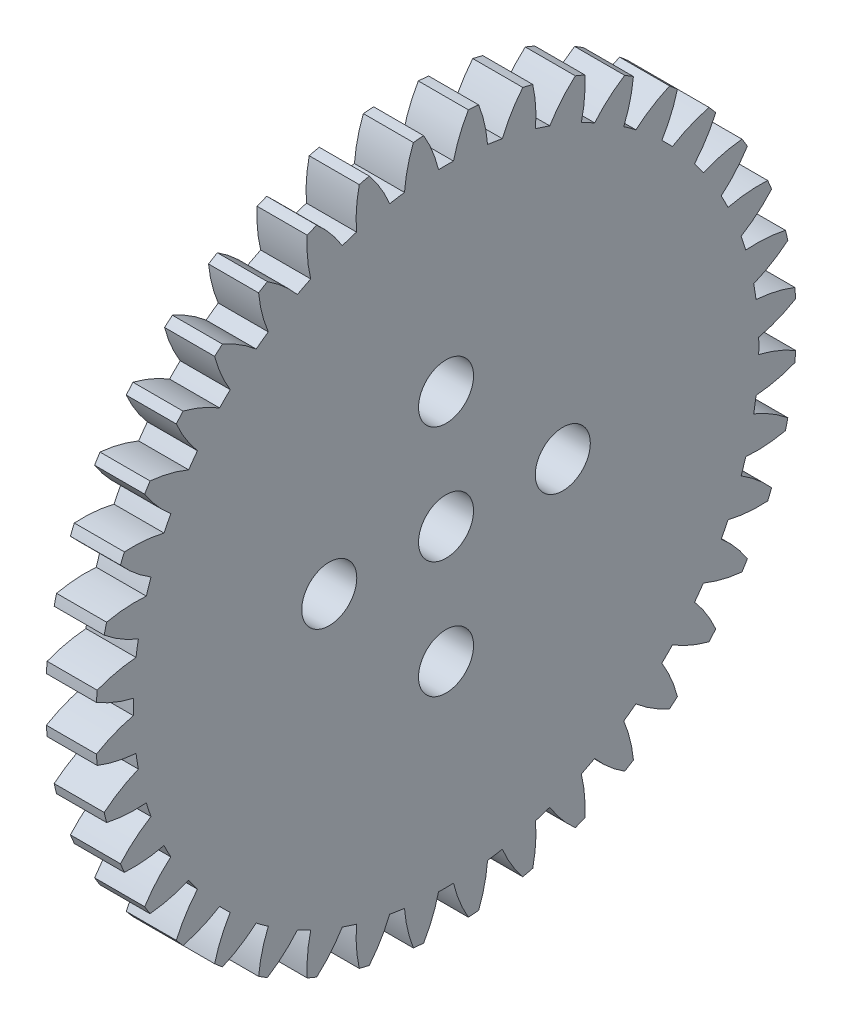
SolidWorks part; units mm, degrees
ref_plane "Plane1" through (0, 0, 0) normal (0, 0, 1) x (1, 0, 0)
ref_plane "Plane2" through (0, 0, 0) normal (0, 1, 0) x (1, 0, 0)
ref_plane "Plane3" through (0, 0, 0) normal (1, 0, 0) x (0, 0, -1)
other "Configuration Table"
sketch "HoldingSke" plane through (0, 0, 0) normal (0, 1, 0) x (1, 0, 0)
  line L0 (0, 0) -> (0.766, -0.6428)
  line L1 (-15, 0) -> (100, 0) construction
  line L2 (0, 0) -> (-2.1039, 2.3779)
  line L3 (0, 0) -> (-11.863, 4.5341)
  line L4 (0, 0) -> (6.6156, 5.5511)
  line L5 (0, 0) -> (-46.8476, -17.4728)
  line L6 (0, 0) -> (-2.4869, -1.6779)
  line L7 (-2.1039, 2.3779) -> (8.6586, 51.2059)
  line L8 (-76.2, 54.61) -> (-76.1, 54.61)
  line L9 (-71.009, 38.7566) -> (-53.1078, 45.2721)
  line L10 (-76.2, 71.12) -> (104.1128, 71.12)
  line L11 (0, 0) -> (-3, 0)
  line L12 (-76.2, 101.6) -> (-76.162, 101.6)
  line L13 (24.9733, 27.94) -> (52.9518, 28.4284)
  line L14 (24.9733, 27.94) -> (24.9743, 27.94)
  line L15 (24.9733, 27.94) -> (100.4006, 29.5858)
  line L16 (-63.627, -1) -> (-12.827, -1)
  circle A0 centre (0, 0) radius 0.5
  circle A1 centre (0, 0) radius 18.749
  circle A2 centre (0, 0) radius 37.5
  circle A3 centre (0, 0) radius 0.5
  dimension "MHD" = 37.498
  dimension "Hub_dia" = 75
  dimension "Bore" = 1
  dimension "MBD" = 1
  dimension "Num_teeth" = 40
  dimension "Pitch" = 1
  dimension "Overall_len" = 50
  dimension "Show_teeth" = 40
  dimension "Thickness" = 3
  dimension "OAL" = 50.0001
  dimension "T_dim" = 0.1
  dimension "Ap" = 20
  dimension "H" = 19.05
  dimension "Pitch_radius" = 180.3128
  dimension "Width" = 3
  dimension "Backlash" = 0.038
  dimension "Addendum_fac" = 1
  dimension "Dedendum_fac" = 1.25
  dimension "Clearance_fac" = 0.25
  dimension "Dedendum_add" = 0.001
  dimension "Module" = 1
sketch "BasProSke" plane through (0, 0, 0) normal (0, 1, 0) x (1, 0, 0)
  line L0 (-10, 0) -> (60, 0) construction
  line L1 (0, 0) -> (0, 21)
  line L2 (0, 0) -> (3, 0)
  line L3 (3, 0) -> (3, 21)
  line L4 (3, 21) -> (0, 21)
  dimension "Thickness" = 3
  dimension "Diameter" = 42
revolve "Base-Revolve" add sketch "BasProSke" angle 360 about L0
sketch "TooCutSke" plane through (0, 0, 0) normal (1, 0, 0) x (0, 0, -1)
  line L1 (0, 0) -> (0, 107) construction
  line L2 (0, 0) -> (-0.8517, 19.9819) construction
  line L3 (0, 0) -> (-3.1363, 39.8509) construction
  line L4 (-0.8517, 19.9819) -> (-1.5682, 19.9255) construction
  arc A0 (0.4487, 18.7436) -> (-0.4487, 18.7436) centre (0, 0) ccw
  arc A1 (1.3547, 20.9817) -> (-1.3547, 20.9817) centre (0, 0) ccw
  circle A2 centre (0, 0) radius 20 construction
  circle A3 centre (0, 0) radius 18.7939 construction
  arc A4 (-0.4487, 18.7436) -> (-1.3547, 20.9817) centre (-8.2322, 16.895) ccw
  arc A5 (1.3547, 20.9817) -> (0.4487, 18.7436) centre (8.2322, 16.895) ccw
  dimension "Root_dia" = 37.498
  dimension "Overcut_dia" = 42.0508
  dimension "Pitch_dia" = 40
  dimension "Base_dia" = 37.5877
  dimension "Flank_rad" = 8
  dimension "Half_ang" = 4.5
  dimension "Half_CT" = 0.7187
extrude "ToothCut" cut sketch "TooCutSke" along normal through all
fillet "Breaks" [suppressed] radius 0.02
fillet "RootFillets" [suppressed] radius 0.251
pattern_circular "TeethCuts" count 40 every 9 about axis through (-10, 0, 0) along (1, 0, 0) of "ToothCut", "RootFillets", "Breaks"
sketch "HubNeaOneSke" plane through (0, 0, 0) normal (-1, 0, 0) x (0, 0, 1)
  circle A0 centre (0, 0) radius 18.749
  dimension "Diameter" = 37.498
extrude "HubNearOne" [suppressed] add sketch "HubNeaOneSke" along normal blind 47.0001
sketch "HubNeaBotSke" plane through (0, 0, 0) normal (-1, 0, 0) x (0, 0, 1)
  circle A0 centre (0, 0) radius 18.749
  dimension "Diameter" = 37.498
extrude "HubNearBoth" [suppressed] add sketch "HubNeaBotSke" along normal blind 23.5
ref_plane "FarPln" through (3, 0, 0) normal (1, 0, 0) x (0, 0, -1)
sketch "HubFarSke" plane through (3, 0, 0) normal (1, 0, 0) x (0, 0, -1)
  circle A0 centre (0, 0) radius 18.749
  dimension "Diameter" = 37.498
extrude "HubFar" [suppressed] add sketch "HubFarSke" along normal blind 23.5
sketch "BorSke" plane through (0, 0, 0) normal (1, 0, 0) x (0, 0, -1)
  circle A0 centre (0, 0) radius 0.5
  dimension "Diameter" = 1
extrude "Bore" cut sketch "BorSke" along normal mid plane 100.0001
sketch "KeySke" plane through (0, 0, 0) normal (1, 0, 0) x (0, 0, -1)
  line L0 (-0.05, 0) -> (-0.05, 0.6)
  line L1 (-0.05, 0.6) -> (0.05, 0.6)
  line L2 (0.05, 0.6) -> (0.05, 0)
  line L3 (0, 0) -> (0, 34) construction
  line L4 (-0.05, 0) -> (0.05, 0)
  dimension "Offset" = 0.6
  dimension "Width" = 0.1
extrude "Keyway" [suppressed] cut sketch "KeySke" along normal mid plane 100.0001
pattern_circular "Keyway2" [suppressed] count 2 every 90 about axis through (-10, 0, 0) along (1, 0, 0)
sketch "草图1" plane through (3, 0, 0) normal (1, 0, 0) x (0, 0, -1)
  circle A0 centre (0, 0) radius 20
  dimension "D1" = 40
sketch "草图2" plane through (3, 0, 0) normal (1, 0, 0) x (0, 0, -1)
  circle A0 centre (0, 0) radius 1.65
  circle A1 centre (0, 0) radius 7 construction
  circle A2 centre (7, 0) radius 1.65
  circle A3 centre (-7, 0) radius 1.65
  circle A4 centre (0, 7) radius 1.65
  circle A5 centre (0, -7) radius 1.65
  dimension "D1" = 3.3
  dimension "D2" = 14
  dimension "D3" = 3.3
  dimension "D4" = 3.3
  dimension "D5" = 3.3
  dimension "D6" = 3.3
extrude "切除-拉伸1" cut sketch "草图2" against normal up to next
equation "' \"Module@HoldingSke\" = 6.35"
equation "' \"Num_teeth@HoldingSke\" = 12"
equation "' \"Ap@HoldingSke\" =  20"
equation "' \"Ap@HoldingSke\" = 20"
equation "' \"Width@HoldingSke\" = 0.5 * 25.4"
equation "' \"Hub_dia@HoldingSke\"= 1 * 25.4"
equation "' \"Hub_dia@HoldingSke\" = 1 * 25.4"
equation "' \"Overall_len@HoldingSke\" = 1.0 * 25.4"
equation "' \"Bore@HoldingSke\" = 0.75 * 25.4"
equation "' \"T_dim@HoldingSke\" = 0.1 * 25.4"
equation "' \"Width@KeySke\" = 0.25 * 25.4"
equation "' \"Show_teeth@HoldingSke\" = 13"
equation "' \"Backlash@HoldingSke\" = 0.009 * 25.4"
equation "' \"Addendum_fac@HoldingSke\" = 1.0"
equation "' \"Dedendum_fac@HoldingSke\" = 1.25"
equation "' \"Dedendum_add@HoldingSke\" = 0.00005 * 25.4"
equation "' \"Clearance_fac@HoldingSke\" = 0.25"
equation "\"Pitch@HoldingSke\" = 1 / \"Module@HoldingSke\""
equation "\"Overcut_dia@TooCutSke\" = (\"Num_teeth@HoldingSke\" + 2 * \"Addendum_fac@HoldingSke\") / \"Pitch@HoldingSke\" + 0.002 * 25.4"
equation "\"Pitch_dia@TooCutSke\" = \"Num_teeth@HoldingSke\" / \"Pitch@HoldingSke\""
equation "\"Base_dia@TooCutSke\" = \"Num_teeth@HoldingSke\" / \"Pitch@HoldingSke\" * cos((\"Ap@HoldingSke\"  * 3.14159265 / 180))"
equation "\"Root_dia@TooCutSke\" = (\"Num_teeth@HoldingSke\" + 2) / \"Pitch@HoldingSke\" - 2 * (\"Addendum_fac@HoldingSke\" + \"Dedendum_fac@HoldingSke\") / \"Pitch@HoldingSke\" - \"Dedendum_add@HoldingSke\" * 2"
equation "\"Half_ang@TooCutSke\" = 180 / \"Num_teeth@HoldingSke\""
equation "\"Half_CT@TooCutSke\" = \"Num_teeth@HoldingSke\" / \"Pitch@HoldingSke\" * sin((3.14159265 / 2 / \"Num_teeth@HoldingSke\")) / 2 - 7 * \"Backlash@HoldingSke\" / 4"
equation "\"Flank_rad@TooCutSke\" = \"Num_teeth@HoldingSke\" / \"Pitch@HoldingSke\" / 5"
equation "\"Radius@RootFillets\" = \"Clearance_fac@HoldingSke\" / \"Pitch@HoldingSke\" + \"Dedendum_add@HoldingSke\""
equation "\"Break_rad@Breaks\" = 0.02 / \"Pitch@HoldingSke\""
equation "\"Thickness@HoldingSke\" = \"Width@HoldingSke\""
equation "\"OAL@HoldingSke\" = \"Thickness@HoldingSke\""
equation "\"MHD@HoldingSke\" = (\"Num_teeth@HoldingSke\" + 2) / \"Pitch@HoldingSke\" - 2 * (\"Addendum_fac@HoldingSke\" + \"Dedendum_fac@HoldingSke\")  / \"Pitch@HoldingSke\" - \"Dedendum_add@HoldingSke\" * 2"
equation "\"MBD@HoldingSke\" = (\"Num_teeth@HoldingSke\" + 2) / \"Pitch@HoldingSke\" - 2 * (\"Addendum_fac@HoldingSke\" + \"Dedendum_fac@HoldingSke\")  / \"Pitch@HoldingSke\" - \"Dedendum_add@HoldingSke\" * 2 - 0.002 * 25.4"
equation "\"MHD@HoldingSke\" = ((sgn( \"MHD@HoldingSke\" - \"Hub_dia@HoldingSke\" )-1)*( \"MHD@HoldingSke\" - \"Hub_dia@HoldingSke\" ))/-2+ \"Hub_dia@HoldingSke\""
equation "\"MBD@HoldingSke\" = ((sgn( \"MBD@HoldingSke\" - \"Bore@HoldingSke\" )-1)*( \"MBD@HoldingSke\" - \"Bore@HoldingSke\" ))/-2+ \"Bore@HoldingSke\""
equation "\"OAL@HoldingSke\" = ((sgn( \"OAL@HoldingSke\" - \"Overall_len@HoldingSke\" )+1)*( \"OAL@HoldingSke\" - \"Overall_len@HoldingSke\" ))/2 + \"Overall_len@HoldingSke\" + 0.000002 * 25.4"
equation "\"Num_teeth@TeethCuts\" = int( \"Show_teeth@HoldingSke\" ) + 1"
equation "\"Num_teeth@TeethCuts\" = ((sgn( \"Num_teeth@TeethCuts\" - \"Num_teeth@HoldingSke\" )-1)*( \"Num_teeth@TeethCuts\" - \"Num_teeth@HoldingSke\" ))/-2+ \"Num_teeth@HoldingSke\""
equation "\"Num_teeth@TeethCuts\" = ((sgn( \"Num_teeth@TeethCuts\" - 2.0)+1)*( \"Num_teeth@TeethCuts\" - 2.0))/2 +2.0"
equation "\"Angle@TeethCuts\" = 360.0 / \"Num_teeth@HoldingSke\""
equation "\"Diameter@BasProSke\" = (\"Num_teeth@HoldingSke\" + 2 * \"Addendum_fac@HoldingSke\") / \"Pitch@HoldingSke\""
equation "\"Thickness@BasProSke\"  = \"Thickness@HoldingSke\""
equation "' \"Fillet_rad@BasProSke\" =  \"Thickness@HoldingSke\" * 0.05"
equation "' \"Fillet_rad@BasProSke\" = \"Thickness@HoldingSke\" * 0.05"
equation "\"MHD@HoldingSke\" = ((sgn( \"MHD@HoldingSke\" - \"Root_dia@TooCutSke\" )-1)*( \"MHD@HoldingSke\" - \"Root_dia@TooCutSke\" ))/-2+ \"Root_dia@TooCutSke\""
equation "\"Diameter@HubNeaOneSke\" = \"MHD@HoldingSke\""
equation "\"Length@HubNearOne\" = \"OAL@HoldingSke\" - \"Thickness@BasProSke\""
equation "\"Diameter@HubNeaBotSke\" = \"MHD@HoldingSke\""
equation "\"Length@HubNearBoth\" = ( \"OAL@HoldingSke\" - \"Thickness@BasProSke\" ) / 2.0"
equation "\"Thickness@FarPln\" = \"Thickness@BasProSke\""
equation "\"Diameter@HubFarSke\" = \"MHD@HoldingSke\""
equation "\"Length@HubFar\" = ( \"OAL@HoldingSke\" - \"Thickness@BasProSke\" ) / 2.0"
equation "\"Diameter@BorSke\" = \"MBD@HoldingSke\""
equation "\"D1@Bore\" = \"OAL@HoldingSke\" * 2.0"
equation "\"D1@Keyway\" = \"OAL@HoldingSke\" * 2.0"
equation "\"Offset@KeySke\" = \"T_dim@HoldingSke\" + \"MBD@HoldingSke\" / 2.0"
